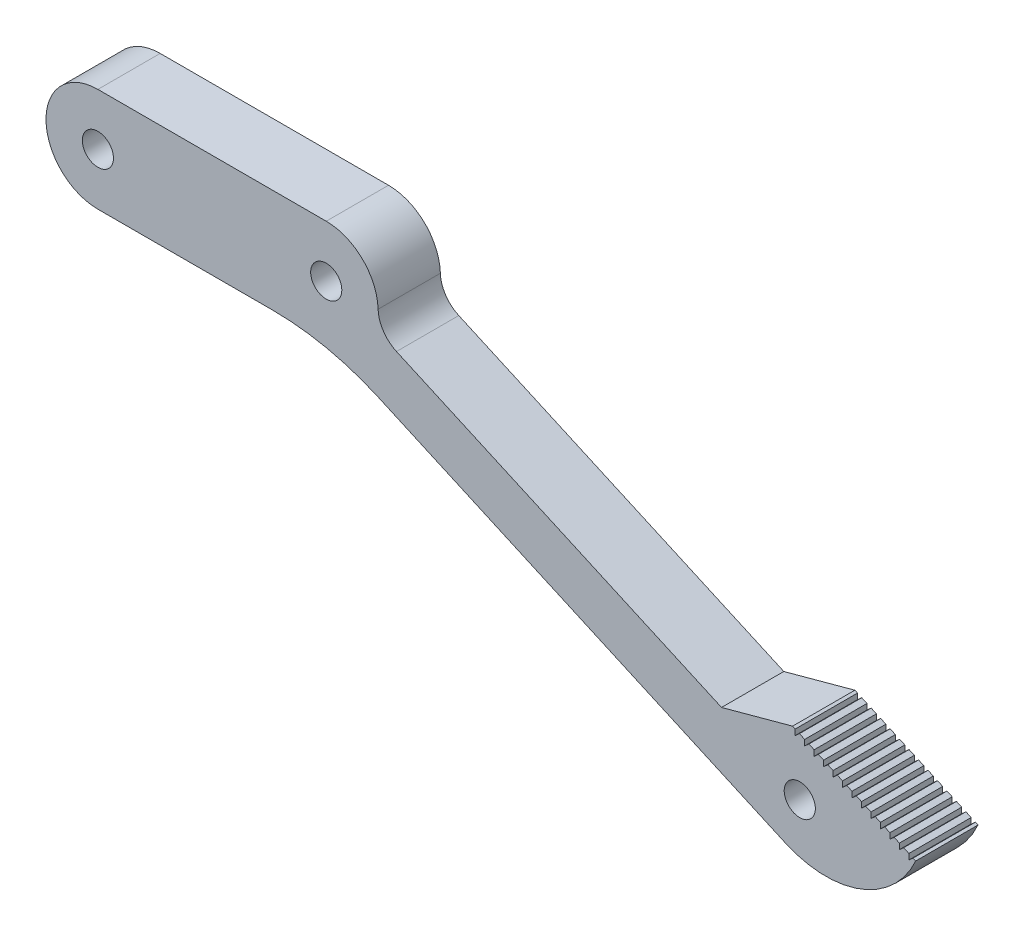
SolidWorks part; units mm, degrees
material "普通碳钢"
ref_plane "前视" through (0, 0, 0) normal (0, 0, 1) x (1, 0, 0)
ref_plane "上视" through (0, 0, 0) normal (0, 1, 0) x (1, 0, 0)
ref_plane "右视" through (0, 0, 0) normal (1, 0, 0) x (0, 0, -1)
sketch "草图1" plane through (0, 0, 0) normal (0, 0, 1) x (1, 0, 0)
  line L0 (-11, 0) -> (11, 0) construction
  line L1 (-11, 5) -> (11, 5)
  line L2 (-11, -5) -> (11, -5)
  arc A0 (-11, 5) -> (-11, -5) centre (-11, 0) ccw
  arc A1 (11, -5) -> (11, 5) centre (11, 0) ccw
  circle A2 centre (-11, 0) radius 1.5
  circle A3 centre (11, 0) radius 1.5
  point P2 (0, 0)
  dimension "D3" = 3
  dimension "D1" = 10
  dimension "D2" = 22
extrude "凸台-拉伸1" add sketch "草图1" along normal blind 6 contours L1 A1 L2 A0 | A2 | A3
sketch "草图2" plane through (0, 0, 6) normal (0, 0, 1) x (1, 0, 0)
  line L0 (17.7688, -2.4866) -> (49.0865, -16.527)
  line L1 (55.24, -24.7653) -> (16.0324, -7.1877)
  line L2 (-11, -5) -> (11, -5) construction
  line L3 (49.0865, -16.527) -> (55.9327, -14.6648)
  line L4 (55.9327, -14.6648) -> (67.7951, -19.983)
  line L5 (11, 0) -> (56.6247, -20.4545) construction
  line L6 (5.8051, -5) -> (11, -5)
  line L7 (67.7951, -19.983) -> (57.3028, -43.3865) construction
  line L8 (67.7951, -19.983) -> (-17.0434, 18.052) construction
  line L9 (0.4545, 25.5498) -> (-11, 0) construction
  arc A0 (11, -5) -> (11, 5) centre (11, 0) ccw construction
  arc A1 (16.0324, -7.1877) -> (5.8051, -5) centre (5.8051, -30) ccw
  arc A2 (11, -5) -> (15.9975, 0.1568) centre (11, 0) ccw
  arc A3 (67.7951, -19.983) -> (55.24, -24.7653) centre (59.1264, -16.0966) cw
  circle A4 centre (56.6247, -20.4545) radius 1.5
  circle A5 centre (-11, 0) radius 1.5 construction
  circle A6 centre (0.4545, 25.5498) radius 1.5 construction
  arc A8 (17.7688, -2.4866) -> (15.9975, 0.1568) centre (18.9961, 0.2508) cw
  dimension "D2" = 3
  dimension "D5" = 13
  dimension "D6" = 8.5
  dimension "D8" = 28
  dimension "D9" = 3
  dimension "D10" = 25
  dimension "D11" = 3
  dimension "D1" = 5
  dimension "D3" = 50
  dimension "D4" = 9.5
  dimension "D7" = 60
extrude "凸台-拉伸2" add sketch "草图2" against normal blind 6
sketch "草图3" plane through (0, 0, 6) normal (0, 0, 1) x (1, 0, 0)
  line L0 (67.1343, -20.2347) -> (35.8024, -6.1879) construction
  line L1 (67.7951, -19.983) -> (55.9327, -14.6648) construction
  line L2 (67.5434, -19.8701) -> (67.1343, -20.2347)
  line L3 (67.1343, -20.2347) -> (67.1343, -19.6867)
  line L4 (67.5434, -19.8701) -> (67.1343, -19.6867) construction
  line L5 (67.3388, -19.7784) -> (67.1343, -20.2347) construction
  line L6 (67.5434, -19.8701) -> (67.1343, -19.6867)
  dimension "D1" = 0.5
  dimension "D2" = 0.5
extrude "切除-拉伸1" cut sketch "草图3" against normal blind 6
pattern_linear "阵列(线性)1" count 13 spacing 1 along (-0.9125, 0.4091, 0) of "切除-拉伸1"
